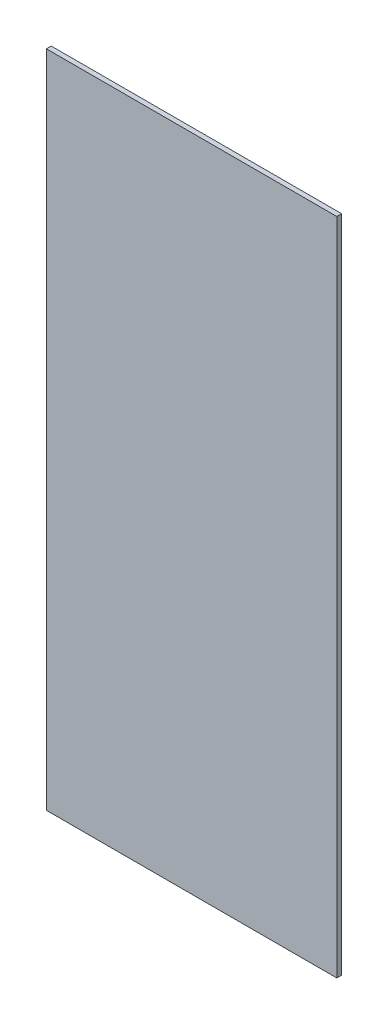
SolidWorks part; units mm, degrees
ref_plane "Front Plane" through (0, 0, 0) normal (0, 0, 1) x (1, 0, 0)
ref_plane "Top Plane" through (0, 0, 0) normal (0, 1, 0) x (1, 0, 0)
ref_plane "Right Plane" through (0, 0, 0) normal (1, 0, 0) x (0, 0, -1)
sketch "Sketch1" plane through (0, 0, 0) normal (0, 0, 1) x (1, 0, 0)
  line L0 (-178, -3) -> (3, -3)
  line L1 (3, -3) -> (3, 408)
  line L2 (3, 408) -> (-178, 408)
  line L3 (-178, 408) -> (-178, -3)
  line L4 (-175, 0) -> (0, 0)
  line L5 (0, 0) -> (0, 405)
  line L6 (0, 405) -> (-175, 405)
  line L7 (-175, 405) -> (-175, 0)
  line L8 (-175, 0) -> (0, 0) construction
  line L9 (0, 0) -> (0, 405) construction
  line L10 (0, 405) -> (-175, 405) construction
  line L11 (-175, 405) -> (-175, 0) construction
  dimension "D1" = 0
  dimension "D2" = 3
extrude "Boss-Extrude1" add sketch "Sketch1" along normal blind 3
